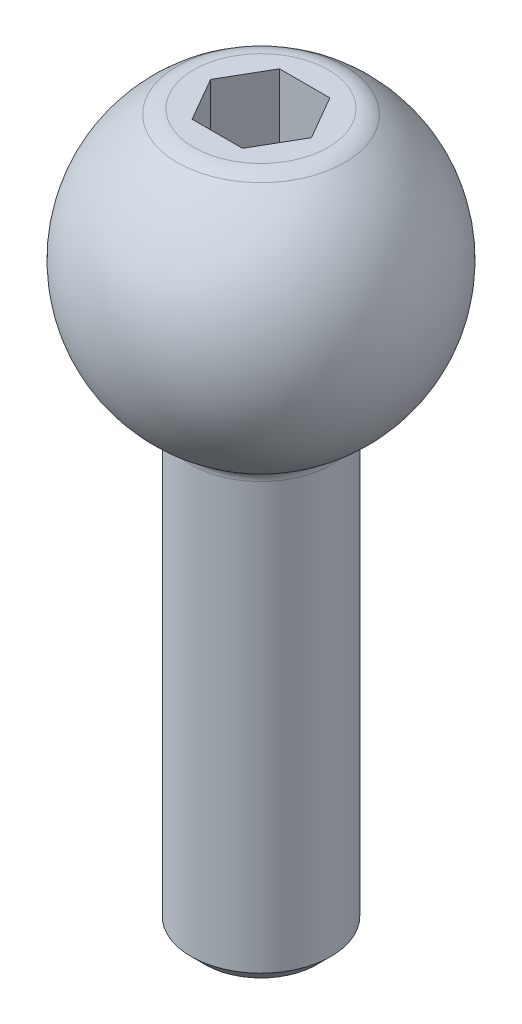
SolidWorks part; units mm, degrees
ref_plane "Front" through (0, 0, 0) normal (0, 0, 1) x (1, 0, 0)
ref_plane "Top" through (0, 0, 0) normal (0, 1, 0) x (1, 0, 0)
ref_plane "Right" through (0, 0, 0) normal (1, 0, 0) x (0, 0, -1)
sketch "Sketch1" plane through (0, 0, 0) normal (0, 0, 1) x (1, 0, 0)
  line L0 (0, -101.5343) -> (0, 4975.1784) construction
  line L1 (-1.905, -3.6616) -> (-1.905, -15.875)
  line L2 (-1.905, -15.875) -> (0, -15.875)
  line L3 (0, 4.1275) -> (0, -15.875)
  arc A0 (0, 4.1275) -> (-1.905, -3.6616) centre (0, 0) ccw
  dimension "D1" = 4.1275
  dimension "D2" = 15.875
  dimension "D3" = 3.81
revolve "Revolve1" add sketch "Sketch1" angle 360 about L0
cosmetic thread "Cosmetic Thread1" parameters "D2"=2.7483
fillet "Fillet1" radius 0.381 1 edges at (1.905, -3.6616, 0)
chamfer "Chamfer1" distance 0.381 1 edges at (1.905, -15.875, 0)
sketch "Sketch2" plane through (0, 0, 0) normal (0, 0, 1) x (1, 0, 0)
  line L0 (1.905, -15.494) -> (1.524, -15.875)
  line L1 (-1.524, -15.875) -> (-1.905, -15.494)
  line L2 (-1.524, -15.875) -> (1.524, -15.875)
  line L3 (-1.905, -3.886) -> (-1.905, -15.494)
  line L4 (1.905, -15.494) -> (1.905, -3.886)
  line L5 (1.905, -15.494) -> (1.905, -3.886) construction
  line L6 (-1.905, -3.886) -> (-1.905, -15.494) construction
  line L7 (-1.524, -15.875) -> (1.524, -15.875) construction
  line L8 (-1.524, -15.875) -> (-1.905, -15.494) construction
  line L9 (1.905, -15.494) -> (1.524, -15.875) construction
  line L10 (-2.0638, 3.5745) -> (2.0638, 3.5745)
  arc A0 (2.0928, -3.5576) -> (1.905, -3.886) centre (2.286, -3.886) ccw
  arc A1 (-1.905, -3.886) -> (-2.0928, -3.5576) centre (-2.286, -3.886) ccw
  arc A2 (2.0928, -3.5576) -> (-2.0928, -3.5576) centre (0, 0) ccw
  arc A3 (2.0928, -3.5576) -> (-2.0928, -3.5576) centre (0, 0) ccw construction
  arc A4 (-1.905, -3.886) -> (-2.0928, -3.5576) centre (-2.286, -3.886) ccw construction
  arc A5 (2.0928, -3.5576) -> (1.905, -3.886) centre (2.286, -3.886) ccw construction
  point P13 (0, 0)
  point P14 (0, 0)
  dimension "D1" = 4.1275
ref_plane "Plane1" through (0, 3.5745, 0) normal (0, 1, 0) x (1, 0, 0)
other "SurfaceCut1"
fillet "Fillet2" radius 0.8128 1 edges at (0, 3.5745, 2.0637)
sketch "Sketch3" plane through (0, 3.5745, 0) normal (0, 1, 0) x (1, 0, 0)
  line L1 (-0.6874, -1.1906) -> (0.6874, -1.1906)
  line L2 (0.6874, -1.1906) -> (1.3748, 0)
  line L3 (1.3748, 0) -> (0.6874, 1.1906)
  line L4 (0.6874, 1.1906) -> (-0.6874, 1.1906)
  line L5 (-0.6874, 1.1906) -> (-1.3748, 0)
  line L6 (-1.3748, 0) -> (-0.6874, -1.1906)
  circle A0 centre (0, 0) radius 1.1906 construction
  dimension "D1" = 2.3813
extrude "Cut-Extrude1" cut sketch "Sketch3" against normal blind 2.54
